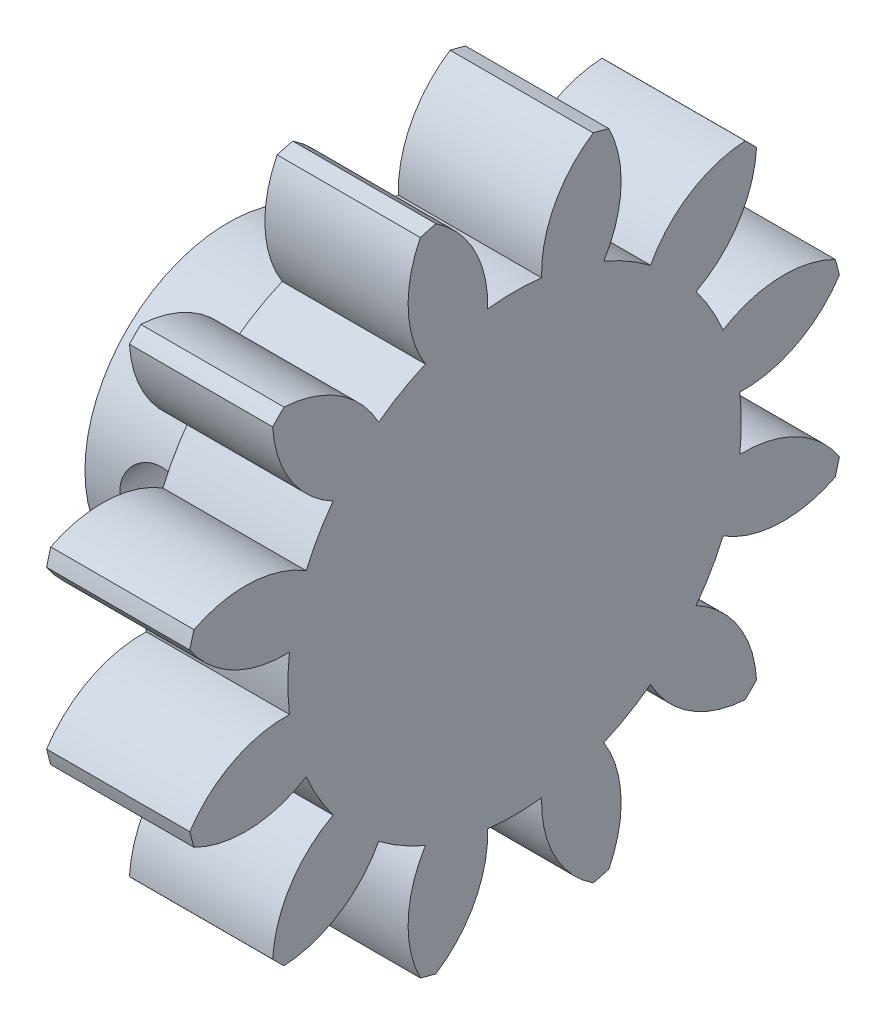
SolidWorks part; units mm, degrees
ref_plane "Plane1" through (0, 0, 0) normal (0, 0, 1) x (1, 0, 0)
ref_plane "Plane2" through (0, 0, 0) normal (0, 1, 0) x (1, 0, 0)
ref_plane "Plane3" through (0, 0, 0) normal (1, 0, 0) x (0, 0, -1)
other "Configuration Table"
sketch "HoldingSke" plane through (0, 0, 0) normal (0, 1, 0) x (1, 0, 0)
  line L0 (0, 0) -> (149.0697, -31.6857)
  line L1 (-15, 0) -> (100, 0) construction
  line L2 (0, 0) -> (-2.1039, 2.3779)
  line L3 (0, 0) -> (-11.863, 4.5341)
  line L4 (0, 0) -> (8.4473, 1.7955)
  line L5 (0, 0) -> (-47.5972, -17.7524)
  line L6 (0, 0) -> (-10.5278, -7.1032)
  line L7 (-2.1039, 2.3779) -> (8.831, 51.9882)
  line L8 (-76.2, 54.61) -> (-54.9402, 54.61)
  line L9 (-71.009, 38.7566) -> (-53.1078, 45.2721)
  line L10 (-76.2, 71.12) -> (104.1128, 71.12)
  line L11 (0, 0) -> (-12.7, 0)
  line L12 (-76.2, 101.6) -> (-76.0298, 101.6)
  line L13 (24.9733, 27.94) -> (52.9518, 28.4284)
  line L14 (24.9733, 27.94) -> (24.9746, 27.94)
  line L15 (24.9733, 27.94) -> (100.4006, 29.5858)
  circle A0 centre (0, 0) radius 9.525
  circle A1 centre (0, 0) radius 20.1071
  circle A2 centre (0, 0) radius 38.1
  circle A3 centre (0, 0) radius 9.525
  dimension "MHD" = 40.2141
  dimension "Hub_dia" = 76.2
  dimension "Bore" = 19.05
  dimension "MBD" = 19.05
  dimension "Num_teeth" = 12
  dimension "Pitch" = 152.4
  dimension "Overall_len" = 50.8
  dimension "Show_teeth" = 12
  dimension "Thickness" = 12.7
  dimension "OAL" = 50.8011
  dimension "T_dim" = 21.2598
  dimension "Ap" = 20
  dimension "H" = 19.05
  dimension "Pitch_radius" = 180.3128
  dimension "Width" = 12.7
  dimension "Backlash" = 0.1702
  dimension "Addendum_fac" = 1
  dimension "Dedendum_fac" = 1.25
  dimension "Clearance_fac" = 0.25
  dimension "Dedendum_add" = 0.0013
sketch "BasProSke" plane through (0, 0, 0) normal (0, 1, 0) x (1, 0, 0)
  line L0 (-10, 0) -> (60, 0) construction
  line L1 (0, 0) -> (0, 29.6333)
  line L2 (0, 0) -> (12.7, 0)
  line L3 (12.7, 0) -> (12.7, 29.6333)
  line L4 (12.7, 29.6333) -> (0, 29.6333)
  dimension "Thickness" = 12.7
  dimension "Diameter" = 59.2667
revolve "Base-Revolve" add sketch "BasProSke" angle 360 about L0
sketch "TooCutSke" plane through (0, 0, 0) normal (1, 0, 0) x (0, 0, -1)
  line L1 (0, 0) -> (0, 107) construction
  line L2 (0, 0) -> (-3.6127, 25.1418) construction
  line L3 (0, 0) -> (-13.0549, 48.7215) construction
  line L4 (-3.6127, 25.1418) -> (-6.5274, 24.3608) construction
  arc A0 (2.3928, 19.9642) -> (-2.3928, 19.9642) centre (0, 0) ccw
  arc A1 (7.0051, 28.8196) -> (-7.0051, 28.8196) centre (0, 0) ccw
  circle A2 centre (0, 0) radius 25.4 construction
  circle A3 centre (0, 0) radius 23.8682 construction
  arc A4 (-2.3928, 19.9642) -> (-7.0051, 28.8196) centre (-12.5471, 20.3042) ccw
  arc A5 (7.0051, 28.8196) -> (2.3928, 19.9642) centre (12.5471, 20.3042) ccw
  dimension "Root_dia" = 40.2141
  dimension "Overcut_dia" = 59.3175
  dimension "Pitch_dia" = 50.8
  dimension "Base_dia" = 47.7364
  dimension "Flank_rad" = 10.16
  dimension "Half_ang" = 15
  dimension "Half_CT" = 3.0176
extrude "ToothCut" cut sketch "TooCutSke" along normal through all
fillet "Breaks" [suppressed] radius 0.0847
fillet "RootFillets" [suppressed] radius 1.0596
pattern_circular "TeethCuts" count 12 every 30 about axis through (-10, 0, 0) along (1, 0, 0) of "ToothCut", "RootFillets", "Breaks"
sketch "HubNeaOneSke" plane through (0, 0, 0) normal (-1, 0, 0) x (0, 0, 1)
  circle A0 centre (0, 0) radius 20.1071
  dimension "Diameter" = 40.2141
extrude "HubNearOne" [suppressed] add sketch "HubNeaOneSke" along normal blind 38.1011
sketch "HubNeaBotSke" plane through (0, 0, 0) normal (-1, 0, 0) x (0, 0, 1)
  circle A0 centre (0, 0) radius 20.1071
  dimension "Diameter" = 40.2141
extrude "HubNearBoth" [suppressed] add sketch "HubNeaBotSke" along normal blind 19.0506
ref_plane "FarPln" through (12.7, 0, 0) normal (1, 0, 0) x (0, 0, -1)
sketch "HubFarSke" plane through (12.7, 0, 0) normal (1, 0, 0) x (0, 0, -1)
  circle A0 centre (0, 0) radius 20.1071
  dimension "Diameter" = 40.2141
extrude "HubFar" [suppressed] add sketch "HubFarSke" along normal blind 19.0506
sketch "Sketch1" plane through (0, 0, 0) normal (-1, 0, 0) x (0, 0, 1)
  circle A0 centre (0, 0) radius 12.7
  circle A1 centre (0, 0) radius 5.715
  dimension "D1" = 25.4
  dimension "D2" = 11.43
extrude "Boss-Extrude1" add sketch "Sketch1" along normal blind 12.7
ref_plane "Plane4" through (0, 0, 13.97) normal (0, 0, 1) x (1, 0, 0)
sketch "Sketch2" plane through (0, 0, 13.97) normal (0, 0, 1) x (1, 0, 0)
  line L0 (0, 2.3928) -> (0, -2.3928) construction
  line L1 (0, 0) -> (-11.6247, 0) construction
  circle A0 centre (-6.35, 0) radius 3.2512
  dimension "D2" = 6.5024
  dimension "D1" = 6.35
extrude "Cut-Extrude1" cut sketch "Sketch2" against normal up to surface (8.255 mm away) up to face at (-12.7, 0, 5.715)
sketch "Sketch4" plane through (0, 0, 0) normal (0, 0, 1) x (1, 0, 0)
  line L0 (0, 2.3928) -> (0, -2.3928) construction
  line L1 (-1.524, 2.7863) -> (-6.35, 5.5726)
  line L2 (-6.35, 5.5726) -> (-11.176, 2.7863)
  line L3 (-11.176, 2.7863) -> (-11.176, -2.7863)
  line L4 (-11.176, -2.7863) -> (-6.35, -5.5726)
  line L5 (-6.35, -5.5726) -> (-1.524, -2.7863)
  line L6 (-1.524, -2.7863) -> (-1.524, 2.7863)
  circle A0 centre (-6.35, 0) radius 4.826 construction
  dimension "D1" = 9.652
extrude "Cut-Extrude2" cut sketch "Sketch4" along normal blind 7.62
equation "' \"Pitch@HoldingSke\" = 4"
equation "' \"Num_teeth@HoldingSke\" = 12"
equation "' \"Ap@HoldingSke\" =  20"
equation "' \"Ap@HoldingSke\" = 20"
equation "' \"Width@HoldingSke\" = 0.5"
equation "' \"Hub_dia@HoldingSke\"= 1"
equation "' \"Hub_dia@HoldingSke\" = 1"
equation "' \"Overall_len@HoldingSke\" = 1.0"
equation "' \"Bore@HoldingSke\" = 0.75"
equation "' \"T_dim@HoldingSke\" = 0.85"
equation "' \"Width@KeySke\" = 0.25"
equation "' \"Show_teeth@HoldingSke\" = 13"
equation "' \"Backlash@HoldingSke\" = 0.009"
equation "' \"Addendum_fac@HoldingSke\" = 1.0"
equation "' \"Dedendum_fac@HoldingSke\" = 1.25"
equation "' \"Dedendum_add@HoldingSke\" = 0.00005"
equation "' \"Clearance_fac@HoldingSke\" = 0.25"
equation "' \"Pitch@HoldingSke\" = 0.5"
equation "' \"Num_teeth@HoldingSke\" = 23"
equation "' \"Show_teeth@HoldingSke\" = 23"
equation "' \"Backlash@HoldingSke\" = 0.0375"
equation "\"Overcut_dia@TooCutSke\" = (\"Num_teeth@HoldingSke\" + 2 * \"Addendum_fac@HoldingSke\") / \"Pitch@HoldingSke\" + 0.002"
equation "\"Pitch_dia@TooCutSke\" = \"Num_teeth@HoldingSke\" / \"Pitch@HoldingSke\""
equation "\"Base_dia@TooCutSke\" = \"Num_teeth@HoldingSke\" / \"Pitch@HoldingSke\" * cos((\"Ap@HoldingSke\"  * 3.14159265 / 180))"
equation "\"Root_dia@TooCutSke\" = (\"Num_teeth@HoldingSke\" + 2) / \"Pitch@HoldingSke\" - 2 * (\"Addendum_fac@HoldingSke\" + \"Dedendum_fac@HoldingSke\") / \"Pitch@HoldingSke\" - \"Dedendum_add@HoldingSke\" * 2"
equation "\"Half_ang@TooCutSke\" = 180 / \"Num_teeth@HoldingSke\""
equation "\"Half_CT@TooCutSke\" = \"Num_teeth@HoldingSke\" / \"Pitch@HoldingSke\" * sin((3.14159265 / 2 / \"Num_teeth@HoldingSke\")) / 2 - 7 * \"Backlash@HoldingSke\" / 4"
equation "\"Flank_rad@TooCutSke\" = \"Num_teeth@HoldingSke\" / \"Pitch@HoldingSke\" / 5"
equation "\"Radius@RootFillets\" = \"Clearance_fac@HoldingSke\" / \"Pitch@HoldingSke\" + \"Dedendum_add@HoldingSke\""
equation "\"Break_rad@Breaks\" = 0.02 / \"Pitch@HoldingSke\""
equation "\"Thickness@HoldingSke\" = \"Width@HoldingSke\""
equation "\"OAL@HoldingSke\" = \"Thickness@HoldingSke\""
equation "\"MHD@HoldingSke\" = (\"Num_teeth@HoldingSke\" + 2) / \"Pitch@HoldingSke\" - 2 * (\"Addendum_fac@HoldingSke\" + \"Dedendum_fac@HoldingSke\")  / \"Pitch@HoldingSke\" - \"Dedendum_add@HoldingSke\" * 2"
equation "\"MBD@HoldingSke\" = (\"Num_teeth@HoldingSke\" + 2) / \"Pitch@HoldingSke\" - 2 * (\"Addendum_fac@HoldingSke\" + \"Dedendum_fac@HoldingSke\")  / \"Pitch@HoldingSke\" - \"Dedendum_add@HoldingSke\" * 2 - 0.002"
equation "\"MHD@HoldingSke\" = ((sgn( \"MHD@HoldingSke\" - \"Hub_dia@HoldingSke\" )-1)*( \"MHD@HoldingSke\" - \"Hub_dia@HoldingSke\" ))/-2+ \"Hub_dia@HoldingSke\""
equation "\"MBD@HoldingSke\" = ((sgn( \"MBD@HoldingSke\" - \"Bore@HoldingSke\" )-1)*( \"MBD@HoldingSke\" - \"Bore@HoldingSke\" ))/-2+ \"Bore@HoldingSke\""
equation "\"OAL@HoldingSke\" = ((sgn( \"OAL@HoldingSke\" - \"Overall_len@HoldingSke\" )+1)*( \"OAL@HoldingSke\" - \"Overall_len@HoldingSke\" ))/2 + \"Overall_len@HoldingSke\" + 0.000002"
equation "\"Num_teeth@TeethCuts\" = int( \"Show_teeth@HoldingSke\" ) + 1"
equation "\"Num_teeth@TeethCuts\" = ((sgn( \"Num_teeth@TeethCuts\" - \"Num_teeth@HoldingSke\" )-1)*( \"Num_teeth@TeethCuts\" - \"Num_teeth@HoldingSke\" ))/-2+ \"Num_teeth@HoldingSke\""
equation "\"Num_teeth@TeethCuts\" = ((sgn( \"Num_teeth@TeethCuts\" - 2.0)+1)*( \"Num_teeth@TeethCuts\" - 2.0))/2 +2.0"
equation "\"Angle@TeethCuts\" = 360.0 / \"Num_teeth@HoldingSke\""
equation "\"Diameter@BasProSke\" = (\"Num_teeth@HoldingSke\" + 2 * \"Addendum_fac@HoldingSke\") / \"Pitch@HoldingSke\""
equation "\"Thickness@BasProSke\"  = \"Thickness@HoldingSke\""
equation "' \"Fillet_rad@BasProSke\" =  \"Thickness@HoldingSke\" * 0.05"
equation "' \"Fillet_rad@BasProSke\" = \"Thickness@HoldingSke\" * 0.05"
equation "\"MHD@HoldingSke\" = ((sgn( \"MHD@HoldingSke\" - \"Root_dia@TooCutSke\" )-1)*( \"MHD@HoldingSke\" - \"Root_dia@TooCutSke\" ))/-2+ \"Root_dia@TooCutSke\""
equation "\"Diameter@HubNeaOneSke\" = \"MHD@HoldingSke\""
equation "\"Length@HubNearOne\" = \"OAL@HoldingSke\" - \"Thickness@BasProSke\""
equation "\"Diameter@HubNeaBotSke\" = \"MHD@HoldingSke\""
equation "\"Length@HubNearBoth\" = ( \"OAL@HoldingSke\" - \"Thickness@BasProSke\" ) / 2.0"
equation "\"Thickness@FarPln\" = \"Thickness@BasProSke\""
equation "\"Diameter@HubFarSke\" = \"MHD@HoldingSke\""
equation "\"Length@HubFar\" = ( \"OAL@HoldingSke\" - \"Thickness@BasProSke\" ) / 2.0"
equation "\"Diameter@BorSke\" = \"MBD@HoldingSke\""
equation "\"D1@Bore\" = \"OAL@HoldingSke\" * 2.0"
equation "\"D1@Keyway\" = \"OAL@HoldingSke\" * 2.0"
equation "\"Offset@KeySke\" = \"T_dim@HoldingSke\" - \"MBD@HoldingSke\" / 2.0"
